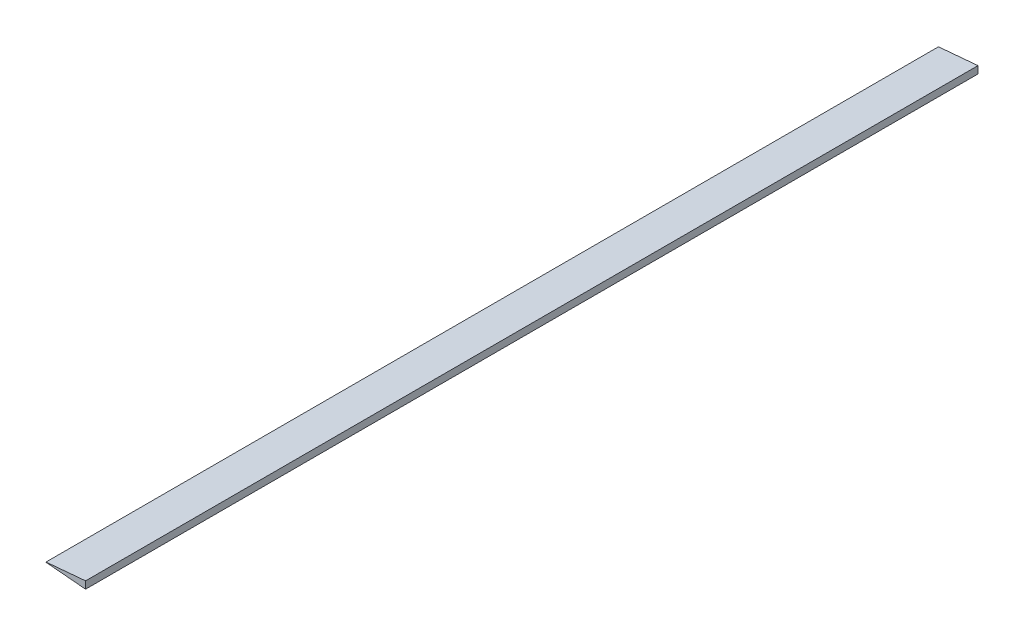
SolidWorks part; units mm, degrees
ref_plane "Front Plane" through (0, 0, 0) normal (0, 0, 1) x (1, 0, 0)
ref_plane "Top Plane" through (0, 0, 0) normal (0, 1, 0) x (1, 0, 0)
ref_plane "Right Plane" through (0, 0, 0) normal (1, 0, 0) x (0, 0, -1)
sketch "Sketch1" plane through (0, 0, 0) normal (0, 0, 1) x (1, 0, 0)
  line L0 (-87.514, 3.4344) -> (-87.514, -3.4344)
  line L1 (-125.02, 0.1181) -> (-125.02, -0.1181)
  spline S0 degree 3 poles (-87.514, 3.4344) (-87.6544, 3.4245) (-89.7388, 3.2775) (-93.6517, 2.9744) (-99.1192, 2.5379) (-104.1854, 2.1093) (-108.795, 1.7019) (-112.8976, 1.3241) (-116.448, 0.9853) (-119.4075, 0.694) (-121.7436, 0.4581) (-123.4308, 0.2844) (-124.4506, 0.178) (-124.9059, 0.1301) (-125.02, 0.1181) knots 0 0 0 0 0.011212 0.166483 0.312686 0.448211 0.571563 0.681381 0.776452 0.855723 0.918312 0.963525 0.990856 1 1 1 1
  spline S1 degree 3 poles (-87.514, -3.4344) (-87.6544, -3.4245) (-89.7388, -3.2775) (-93.6517, -2.9744) (-99.1192, -2.5379) (-104.1854, -2.1093) (-108.795, -1.7019) (-112.8976, -1.3241) (-116.448, -0.9853) (-119.4075, -0.694) (-121.7436, -0.4581) (-123.4308, -0.2844) (-124.4506, -0.178) (-124.9059, -0.1301) (-125.02, -0.1181) knots 0 0 0 0 0.011212 0.166483 0.312686 0.448211 0.571563 0.681381 0.776452 0.855723 0.918312 0.963525 0.990856 1 1 1 1
extrude "Boss-Extrude1" add sketch "Sketch1" along normal mid plane 845.8
